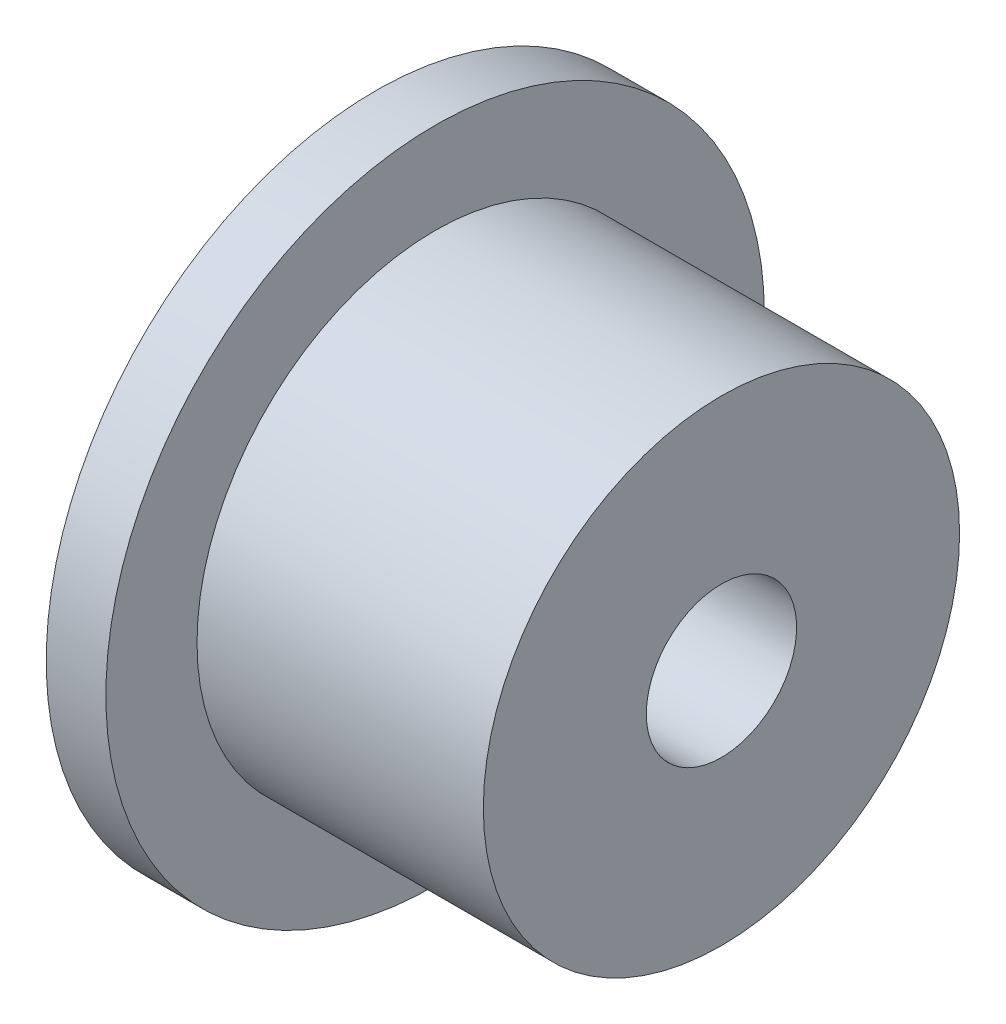
SolidWorks part; units mm, degrees
material "6061 Alloy"
ref_plane "Front Plane" through (0, 0, 0) normal (0, 0, 1) x (1, 0, 0)
ref_plane "Top Plane" through (0, 0, 0) normal (0, 1, 0) x (1, 0, 0)
ref_plane "Right Plane" through (0, 0, 0) normal (1, 0, 0) x (0, 0, -1)
sketch "Sketch1" plane through (0, 0, 0) normal (0, 0, 1) x (1, 0, 0)
  line L0 (0, 0) -> (0, 6.35)
  line L1 (0, 6.35) -> (5.1054, 6.35)
  line L2 (5.1054, 6.35) -> (5.1054, 17.526)
  line L3 (5.1054, 17.526) -> (8.2804, 17.526)
  line L4 (8.2804, 17.526) -> (8.2804, 12.6746)
  line L5 (8.2804, 12.6746) -> (23.5204, 12.6746)
  line L6 (23.5204, 12.6746) -> (23.5204, 0)
  line L7 (23.5204, 0) -> (0, 0) construction
  line L8 (0, 0) -> (23.5204, 0)
  point P3 (5.1054, 11.938)
  dimension "D1" = 25.3492
  dimension "D2" = 12.7
  dimension "D3" = 35.052
  dimension "D4" = 3.175
  dimension "D5" = 5.1054
  dimension "D6" = 15.24
revolve "Revolve1" add sketch "Sketch1" angle 360 about L7
sketch "Sketch2" plane through (0, 0, 0) normal (-1, 0, 0) x (0, 0, 1)
  circle A0 centre (0, 0) radius 4.0005
  dimension "D1" = 8.001
extrude "Cut-Extrude1" cut sketch "Sketch2" against normal through all
sketch "Sketch3" plane through (0, 0, 0) normal (-1, 0, 0) x (0, 0, 1)
  circle A0 centre (0, 0) radius 4.0005
  circle A1 centre (0, 0) radius 6.35
extrude "Boss-Extrude1" add sketch "Sketch3" along normal blind 0.6807
